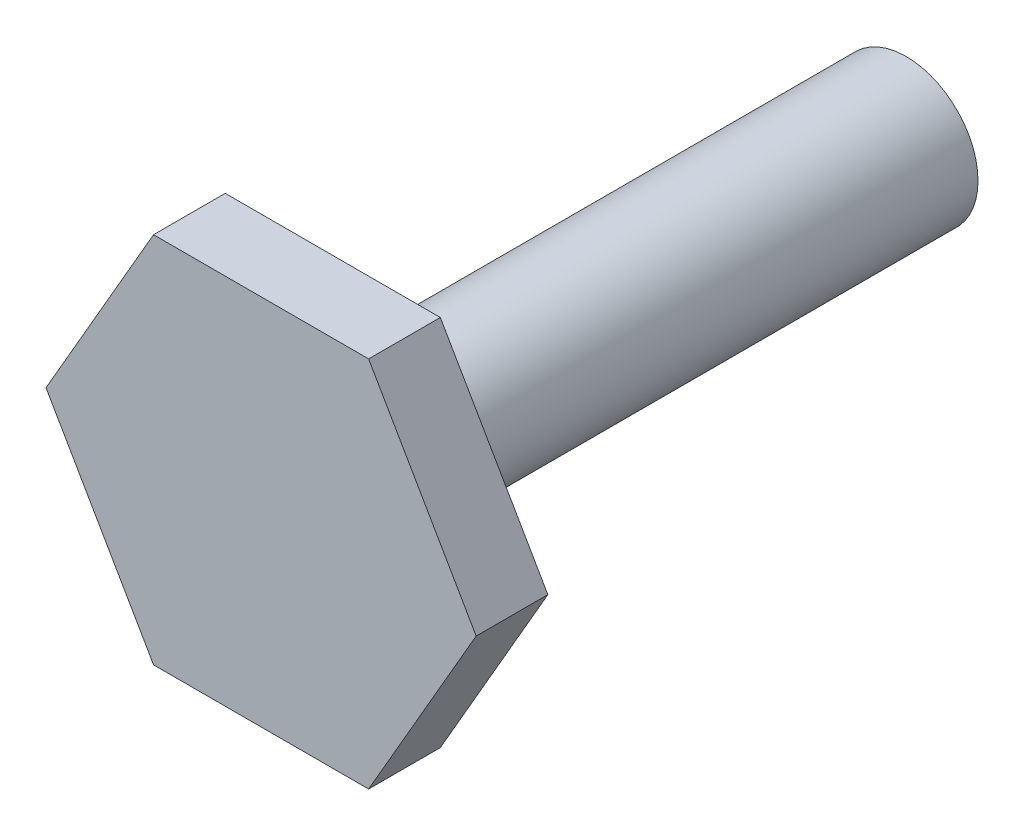
SolidWorks part; units mm, degrees
ref_plane "Front Plane" through (0, 0, 0) normal (0, 0, 1) x (1, 0, 0)
ref_plane "Top Plane" through (0, 0, 0) normal (0, 1, 0) x (1, 0, 0)
ref_plane "Right Plane" through (0, 0, 0) normal (1, 0, 0) x (0, 0, -1)
sketch "Sketch1" plane through (0, 0, 0) normal (0, 0, 1) x (1, 0, 0)
  circle A0 centre (0, 0) radius 3.175
  point P3 (0, 0)
extrude "Boss-Extrude1" add sketch "Sketch1" along normal mid plane 25.4 contours A0
sketch "Sketch2" plane through (0, 0, 12.7) normal (0, 0, 1) x (1, 0, 0)
  line L1 (9.525, 0) -> (4.7625, 8.2489)
  line L2 (4.7625, 8.2489) -> (-4.7625, 8.2489)
  line L3 (-4.7625, 8.2489) -> (-9.525, 0)
  line L4 (-9.525, 0) -> (-4.7625, -8.2489)
  line L5 (-4.7625, -8.2489) -> (4.7625, -8.2489)
  line L6 (4.7625, -8.2489) -> (9.525, 0)
  circle A0 centre (0, 0) radius 8.2489 construction
  dimension "D1" = 9.525
extrude "Boss-Extrude3" add sketch "Sketch2" along normal blind 3.175
